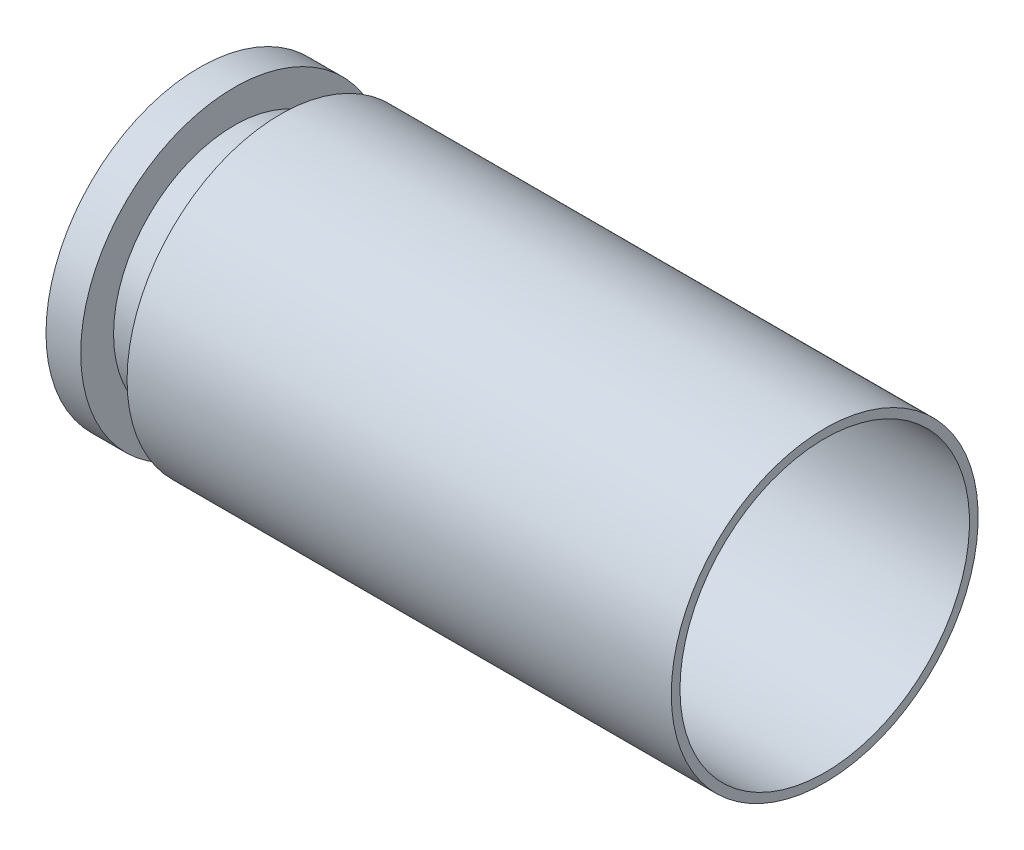
SolidWorks part; units mm, degrees
ref_plane "Plano frontal" through (0, 0, 0) normal (0, 0, 1) x (1, 0, 0)
ref_plane "Plano superior" through (0, 0, 0) normal (0, 1, 0) x (1, 0, 0)
ref_plane "Plano direito" through (0, 0, 0) normal (1, 0, 0) x (0, 0, -1)
sketch "Esboço1" plane through (0, 0, 0) normal (0, 0, 1) x (1, 0, 0)
  line L0 (0, 0) -> (30.4288, 0) construction
  line L1 (4.2, 1) -> (4.2, 5)
  line L3 (21.6, 5.3) -> (2.8, 5.3)
  line L4 (2.8, 5.3) -> (2.8, 4.1664)
  line L5 (2.8, 4.1664) -> (1.2, 4.1664)
  line L6 (1.2, 4.1664) -> (1.2, 5.3)
  line L7 (1.2, 5.3) -> (0, 5.3)
  line L8 (0, 5.3) -> (0, 2.26)
  line L9 (0, 2.26) -> (3, 2.26)
  line L10 (3, 2.26) -> (3, 1)
  line L11 (3, 1) -> (4.2, 1)
  line L13 (21.6, 5.3) -> (21.6, 5)
  line L14 (21.6, 5) -> (4.2, 5)
  dimension "D1" = 1.2
  dimension "D2" = 1.6
  dimension "D3" = 18.8
  dimension "D4" = 3.04
  dimension "D5" = 0.3
  dimension "D6" = 1
  dimension "D7" = 3
  dimension "D9" = 1.1336
  dimension "D10" = 4.3
  dimension "D11" = 5.3
  dimension "D12" = 4.2
  dimension "D13" = 1.2
revolve "Revolução1" add sketch "Esboço1" angle 360 about L0
